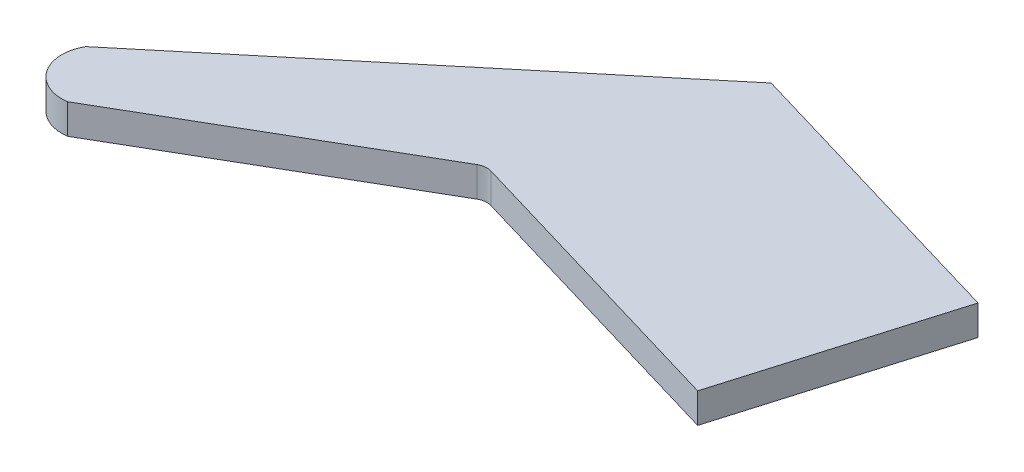
SolidWorks part; units mm, degrees
material "6061 Alloy"
ref_plane "Front Plane" through (0, 0, 0) normal (0, 0, 1) x (1, 0, 0)
ref_plane "Top Plane" through (0, 0, 0) normal (0, 1, 0) x (1, 0, 0)
ref_plane "Right Plane" through (0, 0, 0) normal (1, 0, 0) x (0, 0, -1)
sketch "Sketch1" plane through (0, 0, 0) normal (0, 1, 0) x (1, 0, 0)
  line L1 (22.9946, -31.525) -> (-18.2047, -55.4154)
  line L4 (81.9229, -10.7327) -> (71.7331, -45.1328)
  line L5 (71.7331, -45.1328) -> (24.9902, -31.2869)
  line L6 (81.9229, -10.7327) -> (35.1799, 3.1132)
  line L7 (35.1799, 3.1132) -> (-24.3516, -46.3783)
  arc A0 (-18.2047, -55.4154) -> (-24.3516, -46.3783) centre (-19.075, -49.3983) cw
  arc A2 (22.9946, -31.525) -> (24.9902, -31.2869) centre (24.2688, -33.7223) cw
  dimension "D1" = 2.54
  dimension "D2" = 35.8775
  dimension "D3" = 47.625
extrude "Boss-Extrude1" add sketch "Sketch1" along normal blind 4.7625
